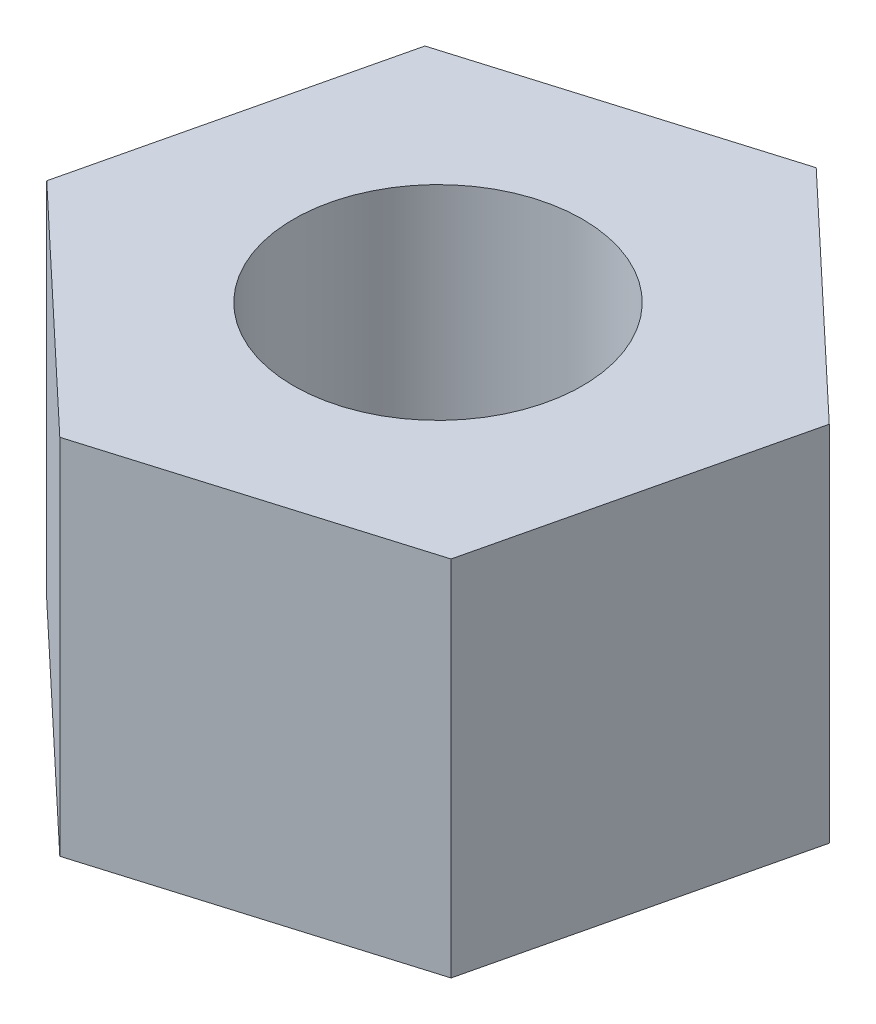
SolidWorks part; units mm, degrees
ref_plane "Front Plane" through (0, 0, 0) normal (0, 0, 1) x (1, 0, 0)
ref_plane "Top Plane" through (0, 0, 0) normal (0, 1, 0) x (1, 0, 0)
ref_plane "Right Plane" through (0, 0, 0) normal (1, 0, 0) x (0, 0, -1)
sketch "Sketch1" plane through (0, 0, 0) normal (0, 1, 0) x (1, 0, 0)
  line L1 (-8.8923, 1.1432) -> (-7.6258, 6.4946)
  line L2 (-7.6258, 6.4946) -> (-11.627, 10.2672)
  line L3 (-11.627, 10.2672) -> (-16.8947, 8.6883)
  line L4 (-16.8947, 8.6883) -> (-18.1613, 3.3369)
  line L5 (-18.1613, 3.3369) -> (-14.1601, -0.4357)
  line L6 (-14.1601, -0.4357) -> (-8.8923, 1.1432)
  circle A0 centre (-12.8935, 4.9158) radius 4.7625 construction
  dimension "D1" = 9.525
extrude "Boss-Extrude1" add sketch "Sketch1" along normal blind 6.35
hole_wizard "#8 (0.199) Diameter Hole1" positions "Sketch2" profile "Sketch3" hole size "#8" standard "ANSI Inch" end condition through all
sketch "Sketch2" plane through (0, 6.35, 0) normal (0, 1, 0) x (1, 0, 0)
  line L0 (-16.8947, 8.6883) -> (-8.8923, 1.1432) construction
  point P7 (-12.8935, 4.9158)
sketch "Sketch3" plane through (-12.8935, 6.35, -4.9158) normal (1, 0, 0) x (0, 0, 1)
  line L0 (0, 0) -> (0, 6.35)
  line L1 (0, 6.35) -> (2.5273, 6.35)
  line L2 (2.5273, 6.35) -> (2.5273, 0)
  line L5 (2.5273, 0) -> (0, 0)
  line L11 (0, -6.35) -> (0, 107.95) construction
  dimension "Thru Hole Dia." = 5.0546
  dimension "Thru Hole Depth" = 6.35
